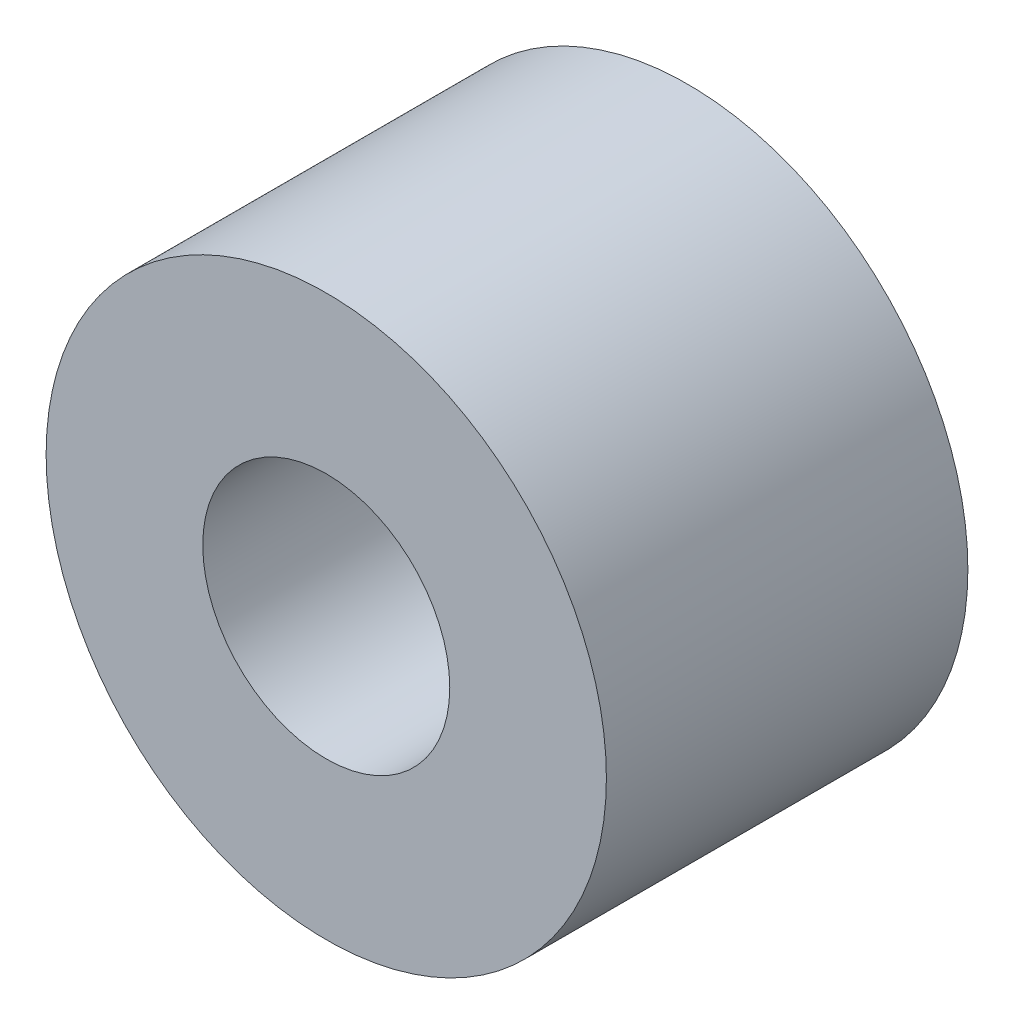
SolidWorks part; units mm, degrees
ref_plane "Front Plane" through (0, 0, 0) normal (0, 0, 1) x (1, 0, 0)
ref_plane "Top Plane" through (0, 0, 0) normal (0, 1, 0) x (1, 0, 0)
ref_plane "Right Plane" through (0, 0, 0) normal (1, 0, 0) x (0, 0, -1)
sketch "Sketch1" plane through (0, 0, 0) normal (0, 0, 1) x (1, 0, 0)
  circle A0 centre (0, 0) radius 13.95
  circle A1 centre (0, 0) radius 6.15
  dimension "D1" = 27.9
  dimension "D2" = 12.3
extrude "Boss-Extrude1" add sketch "Sketch1" along normal blind 18
